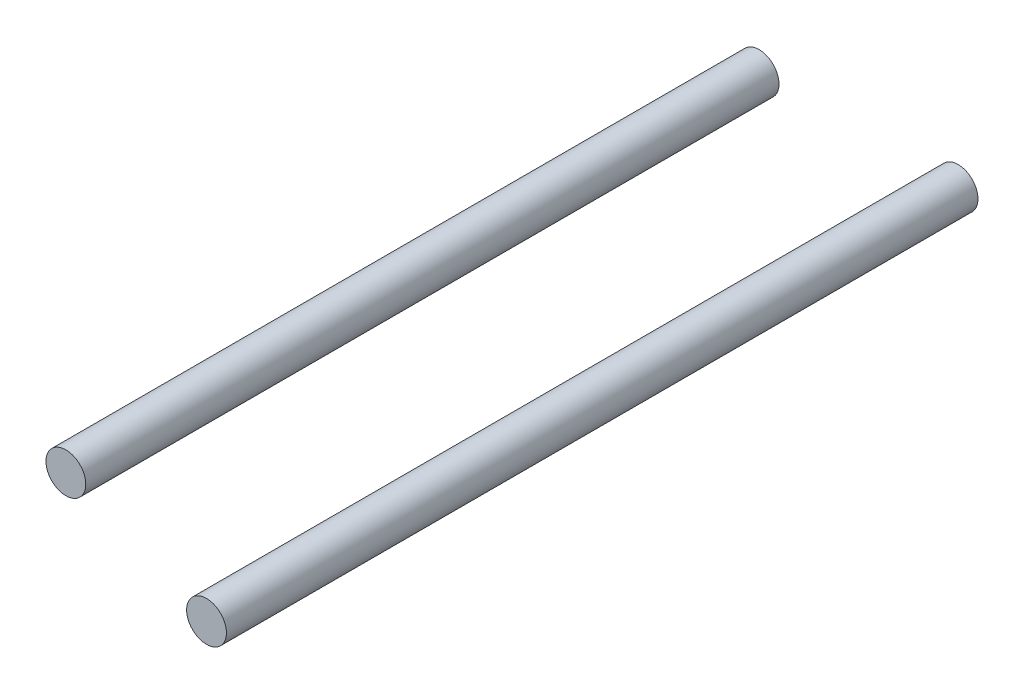
SolidWorks part; units mm, degrees
ref_plane "正面" through (0, 0, 0) normal (0, 0, 1) x (1, 0, 0)
ref_plane "平面" through (0, 0, 0) normal (0, 1, 0) x (1, 0, 0)
ref_plane "右側面" through (0, 0, 0) normal (1, 0, 0) x (0, 0, -1)
sketch "ｽｹｯﾁ1" plane through (0, 0, 0) normal (0, 0, 1) x (1, 0, 0)
  line L0 (-15, 0) -> (15, 0) construction
  circle A0 centre (-15, 0) radius 3
  circle A1 centre (15, 0) radius 3
  dimension "D2" = 6
  dimension "D1" = 30
extrude "ﾎﾞｽ - 押し出し1" add sketch "ｽｹｯﾁ1" along normal blind 104.5
sketch "ｽｹｯﾁ2" plane through (0, 0, 104.5) normal (0, 0, 1) x (1, 0, 0)
  circle A1 centre (15, 0) radius 3
  circle A2 centre (15, 0) radius 3
  dimension "D1" = 0
extrude "ﾎﾞｽ - 押し出し2" add sketch "ｽｹｯﾁ2" along normal blind 8.8
